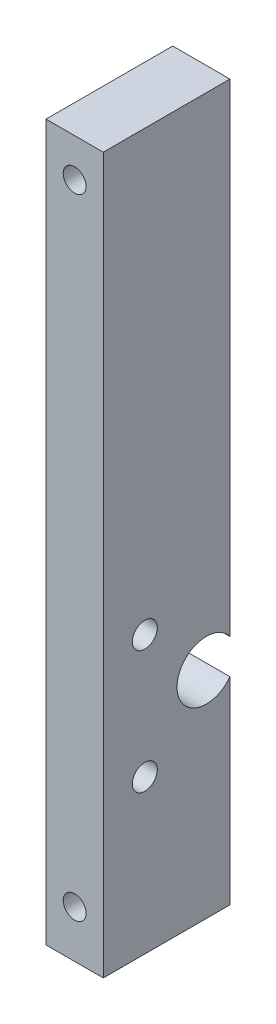
SolidWorks part; units mm, degrees
material "6061-T6 (SS)"
ref_plane "前视基准面" through (0, 0, 0) normal (0, 0, 1) x (1, 0, 0)
ref_plane "上视基准面" through (0, 0, 0) normal (0, 1, 0) x (1, 0, 0)
ref_plane "右视基准面" through (0, 0, 0) normal (1, 0, 0) x (0, 0, -1)
other "Configuration Table"
sketch "草图1" plane through (0, 0, 0) normal (0, 0, 1) x (1, 0, 0)
  line L1 (-4.3, -4.3) -> (-0.3, -4.3)
  line L2 (-4.3, -4.3) -> (-4.3, 45.68)
  line L3 (-4.3, 45.68) -> (-0.3, 45.68)
  line L4 (-0.3, -4.3) -> (-0.3, 45.68)
  dimension "D1" = 0.3
  dimension "D2" = 4.3
  dimension "D3" = 45.68
  dimension "D4" = 4.3
extrude "Left_RF_Plate" add sketch "草图1" along normal blind 8.8519
move or copy body "Stock_Z_Position" bodies to move or copy 106 copy no translate (0, 0, 2.2481) parameters "D1"=0, "D2"=0, "D3"=2.2481
sketch "草图2" plane through (0, 0, 11.1) normal (0, 0, 1) x (1, 0, 0)
  circle A0 centre (-2.3, -1) radius 0.8
  circle A1 centre (-2.3, 43) radius 0.8
  dimension "D1" = 1.6
  dimension "D2" = 2.3
  dimension "D3" = 43
  dimension "D4" = 1
extrude "Frame_2xD1p6_Through" cut sketch "草图2" against normal through all
cosmetic thread "Frame_M2_Through_Cosmetic_1" parameters "D2"=2
cosmetic thread "Frame_M2_Through_Cosmetic_2" parameters "D2"=2
sketch "草图3" plane through (-4.3, 0, 0) normal (-1, 0, 0) x (0, 0, 1)
  circle A0 centre (3.8995, 10.725) radius 2.05
  dimension "D1" = 4.1
  dimension "D2" = 3.8995
  dimension "D3" = 10.725
extrude "SMA_Center_D4p1" cut sketch "草图3" against normal blind 4
sketch "草图4" plane through (-4.3, 0, 0) normal (-1, 0, 0) x (0, 0, 1)
  circle A0 centre (8.1995, 6.425) radius 0.875
  circle A1 centre (8.1995, 15.025) radius 0.875
  dimension "D1" = 1.75
  dimension "D2" = 8.1995
  dimension "D3" = 6.425
  dimension "D4" = 15.025
extrude "SMA_Upper_2xD1p75_Through" cut sketch "草图4" against normal through all
cosmetic thread "SMA_Upper_Cosmetic_1" parameters "D2"=2.2
cosmetic thread "SMA_Upper_Cosmetic_2" parameters "D2"=2.2
